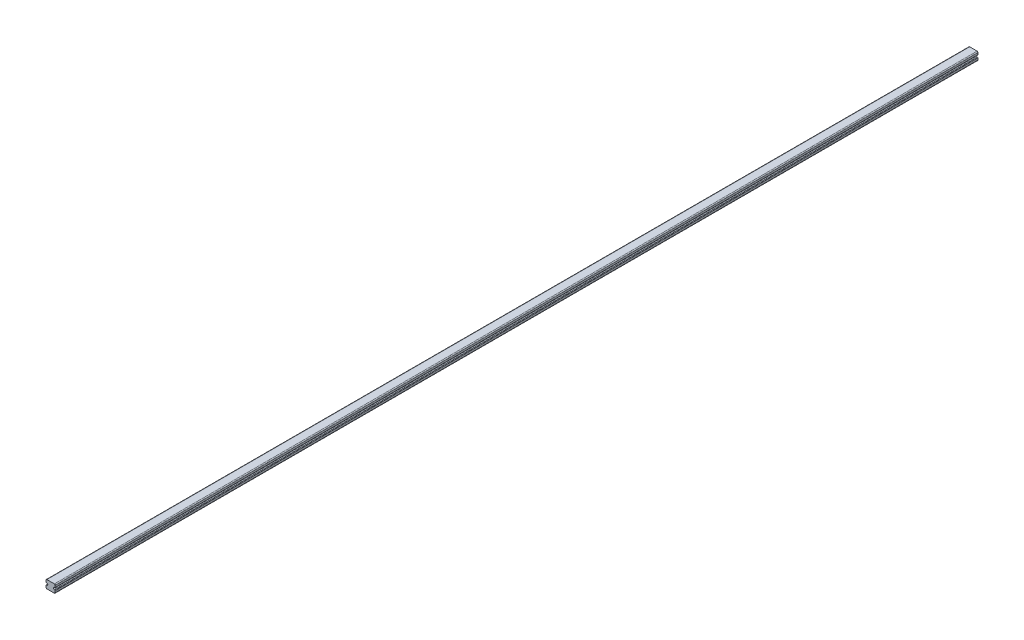
SolidWorks part; units mm, degrees
ref_plane "Front Plane" through (0, 0, 0) normal (0, 0, 1) x (1, 0, 0)
ref_plane "Top Plane" through (0, 0, 0) normal (0, 1, 0) x (1, 0, 0)
ref_plane "Right Plane" through (0, 0, 0) normal (1, 0, 0) x (0, 0, -1)
sketch "Sketch1" plane through (0, 0, 0) normal (0, 0, 1) x (1, 0, 0)
  line L0 (0, 8.75) -> (0, -8.75) construction
  line L1 (-8, -8.75) -> (8, -8.75)
  line L2 (-10, -6.75) -> (-10, -3)
  line L3 (-8, 8.75) -> (8, 8.75)
  line L4 (10, -6.75) -> (10, -3)
  line L5 (-10, -8.75) -> (10, 8.75) construction
  line L6 (-10, 8.75) -> (10, -8.75) construction
  line L7 (0, 0) -> (-19.1226, 0) construction
  line L8 (-8, 2) -> (-9, 2)
  line L9 (-8, -2) -> (-9, -2)
  line L10 (-10, 3) -> (-10, 6.75)
  line L11 (8, -2) -> (9, -2)
  line L12 (8, 2) -> (9, 2)
  line L13 (10, 3) -> (10, 6.75)
  arc A0 (-8, -2) -> (-8, 2) centre (-8, 0) ccw
  arc A1 (-8, -8.75) -> (-10, -6.75) centre (-8, -6.75) cw
  arc A2 (10, -6.75) -> (8, -8.75) centre (8, -6.75) cw
  arc A3 (10, 6.75) -> (8, 8.75) centre (8, 6.75) ccw
  arc A4 (-8, 8.75) -> (-10, 6.75) centre (-8, 6.75) ccw
  arc A5 (-10, -3) -> (-9, -2) centre (-9, -3) cw
  arc A6 (-9, 2) -> (-10, 3) centre (-9, 3) cw
  arc A7 (10, -3) -> (9, -2) centre (9, -3) ccw
  arc A8 (8, -2) -> (8, 2) centre (8, 0) cw
  arc A9 (9, 2) -> (10, 3) centre (9, 3) ccw
  point P0 (0, 0)
  point P32 (-10, 2)
  dimension "D3" = 2
  dimension "D4" = 1
  dimension "D5" = 1
  dimension "D1" = 17.5
  dimension "D2" = 20
extrude "Boss-Extrude1" add sketch "Sketch1" along normal blind 2000
sketch "Sketch2" plane through (0, 0, 0) normal (0, 1, 0) x (1, 0, 0)
  line L0 (0, -2000) -> (0, 89.2875) construction
  line L1 (8, -2000) -> (-8, -2000) construction
